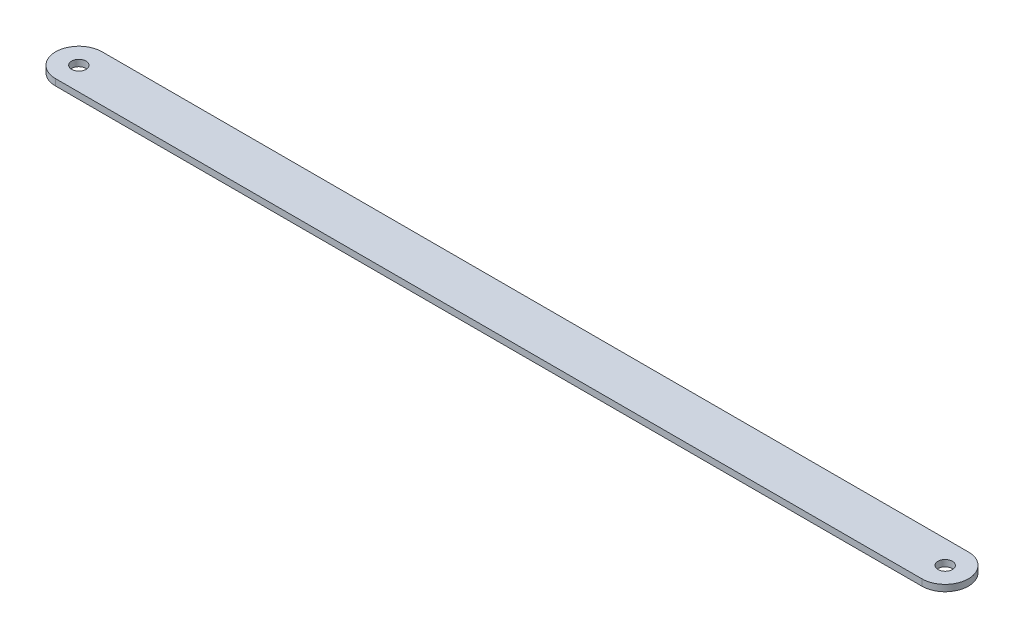
SolidWorks part; units mm, degrees
ref_plane "Front Plane" through (0, 0, 0) normal (0, 0, 1) x (1, 0, 0)
ref_plane "Top Plane" through (0, 0, 0) normal (0, 1, 0) x (1, 0, 0)
ref_plane "Right Plane" through (0, 0, 0) normal (1, 0, 0) x (0, 0, -1)
sketch "Sketch1" plane through (0, 0, 0) normal (0, 1, 0) x (1, 0, 0)
  line L0 (-270, 0) -> (0, 0) construction
  line L1 (-270, -14.5) -> (0, -14.5)
  line L2 (0, 340) -> (0, -14.5)
  line L3 (0, 5.5) -> (-159.9638, 5.5) construction
  line L4 (-159.9638, 5.5) -> (-159.9638, 310) construction
  line L5 (-159.9638, 310) -> (0.0362, 310) construction
  line L6 (-175.5, 384.5) -> (51.2761, 384.5) construction
  line L7 (-175.4638, 340) -> (0, 340)
  line L8 (-189.9638, 325.5) -> (-189.9638, 225.6066)
  line L9 (-229.9638, 14.5) -> (-270, 14.5)
  line L10 (-189.9638, 195.6066) -> (-189.9638, 54.5)
  line L11 (-189.9638, 54.5) -> (-229.9638, 14.5)
  circle A0 centre (-270, 0) radius 4.5
  arc A1 (-270, -14.5) -> (-270, 14.5) centre (-270, 0) cw
  circle A2 centre (-175.4638, 325.5) radius 4.5
  arc A3 (-175.4638, 340) -> (-189.9638, 325.5) centre (-175.4638, 325.5) ccw
  circle A4 centre (-189.9638, 210.6066) radius 6.5
  circle A5 centre (-180.2138, 210.6066) radius 1.75
  circle A6 centre (-189.9638, 220.4066) radius 1.75
  circle A7 centre (-189.9638, 200.8066) radius 1.75
  circle A8 centre (-199.7138, 210.6066) radius 1.75
  arc A9 (-189.9638, 195.6066) -> (-189.9638, 225.6066) centre (-189.9638, 210.6066) cw
  point P18 (-189.9638, 14.5)
  dimension "D2" = 9
  dimension "D3" = 9
  dimension "D7" = 10
  dimension "D10" = 10
  dimension "D13" = 13
  dimension "D14" = 3.5
  dimension "D19" = 15
  dimension "D1" = 270
  dimension "D4" = 160
  dimension "D5" = 304.5
  dimension "D6" = 20
  dimension "D8" = 30
  dimension "D9" = 30
  dimension "D11" = 44.5
  dimension "D12" = 311
  dimension "D15" = 19.5
  dimension "D16" = 9.75
  dimension "D17" = 9.8
  dimension "D18" = 9.8
extrude "Boss-Extrude1" add sketch "Sketch1" along normal blind 4
mirror "Mirror1" about plane through (0, 4, -340) normal (-1, 0, 0) of "Boss-Extrude1"
sketch "Sketch2" plane through (0, 4, 0) normal (0, 1, 0) x (1, 0, 0)
  line L0 (-270, -14.5) -> (270, -14.5) construction
  circle A0 centre (0, 305.5) radius 2
  point P4 (0, -14.5)
  dimension "D1" = 4
  dimension "D2" = 320
extrude "Cut-Extrude1" cut sketch "Sketch2" against normal blind 4
sketch "Sketch3" plane through (0, 4, 0) normal (0, 1, 0) x (1, 0, 0)
  line L0 (-229.9638, 14.5) -> (229.9638, 14.5)
  line L1 (229.9638, 14.5) -> (229.9638, 385.2981)
  line L2 (229.9638, 385.2981) -> (-229.9638, 385.2981)
  line L3 (-229.9638, 385.2981) -> (-229.9638, 14.5)
extrude "Cut-Extrude2" cut sketch "Sketch3" against normal blind 10
